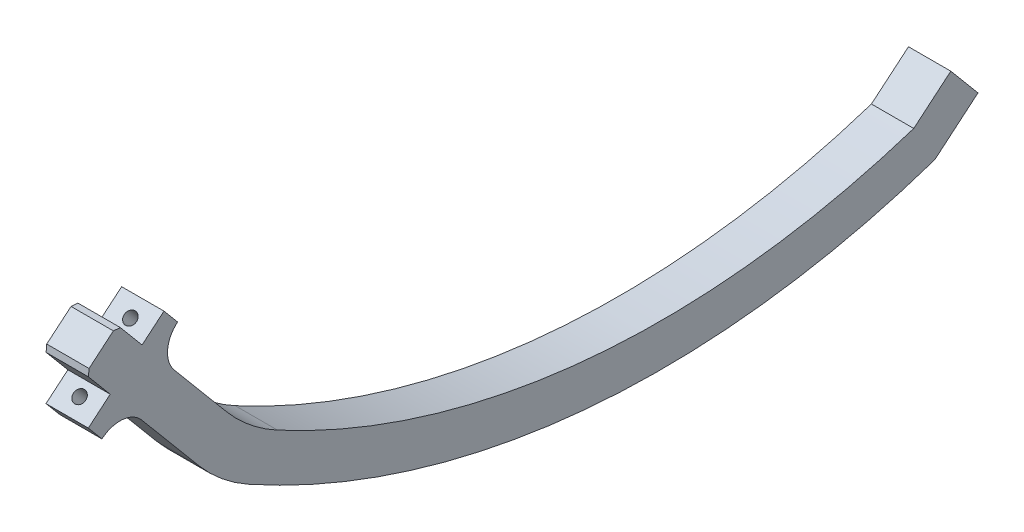
SolidWorks part; units mm, degrees
ref_plane "Ebene vorne" through (0, 0, 0) normal (0, 0, 1) x (1, 0, 0)
ref_plane "Ebene oben" through (0, 0, 0) normal (0, 1, 0) x (1, 0, 0)
ref_plane "Ebene rechts" through (0, 0, 0) normal (1, 0, 0) x (0, 0, -1)
sketch "Skizze1" plane through (0, 0, 0) normal (1, 0, 0) x (0, 0, -1)
  line L0 (0, 12) -> (-233.4212, 12) construction
  line L1 (-240, 65) -> (-230.7357, 72.7737)
  line L2 (0, 12) -> (-3.7358, 23.4037)
  line L3 (0, 12) -> (0, 39.1297) construction
  line L4 (0, 0) -> (-218.6687, 0) construction
  arc A0 (0, 12) -> (-240, 65) centre (-75.176, 241.4765) cw
  arc A1 (-3.7358, 23.4037) -> (-230.7357, 72.7737) centre (-75.176, 241.4765) cw
  dimension "D1" = 53
  dimension "D2" = 240
  dimension "D3" = 40
  dimension "D4" = 12
  dimension "D5" = 12
extrude "Aufsatz-Linear austragen1" add sketch "Skizze1" along normal blind 12
sketch "Skizze4" plane through (0, 0, 0) normal (1, 0, 0) x (0, 0, -1)
  line L0 (-230.7357, 72.7737) -> (-240, 65) construction
  line L2 (-3.7358, 23.4037) -> (6.769, 32.2183)
  line L3 (6.769, 32.2183) -> (14.4825, 23.0258)
  line L4 (14.4825, 23.0258) -> (2.2258, 12.7411)
  line L5 (-3.7358, 23.4037) -> (0, 12)
  arc A0 (0, 12) -> (2.2258, 12.7411) centre (-75.176, 241.4765) ccw
  arc A4 (-240, 65) -> (0, 12) centre (-75.176, 241.4765) ccw construction
  dimension "D1" = 16
  dimension "D2" = 12
extrude "Aufsatz-Linear austragen3" add sketch "Skizze4" along normal blind 12
sketch "Skizze5" plane through (12, 0, 0) normal (1, 0, 0) x (0, 0, -1)
  line L0 (-231.6625, 71.996) -> (-222.47, 79.7094)
  line L1 (-230.7357, 72.7737) -> (-232.109, 74.04) construction
  line L2 (-231.6625, 71.996) -> (-220.0923, 58.2072)
  line L3 (-230.7357, 72.7737) -> (-240, 65) construction
  line L4 (-222.47, 79.7094) -> (-210.8998, 65.9206)
  line L5 (-220.0923, 58.2072) -> (-192.9483, 44.5269)
  line L6 (-220.0923, 58.2072) -> (-211.3409, 65.5505) construction
  line L7 (-210.8998, 65.9206) -> (-192.9483, 44.5269)
  arc A6 (-230.7357, 72.7737) -> (-3.7358, 23.4037) centre (-75.176, 241.4765) ccw construction
  dimension "D1" = 12
  dimension "D2" = 1.2
  dimension "D3" = 18
extrude "Aufsatz-Linear austragen4" add sketch "Skizze5" against normal up to surface (12 mm away) up to face at (0, 27.4794, 77.4862)
sketch "Skizze6" plane through (12, 0, 0) normal (1, 0, 0) x (0, 0, -1)
  line L0 (-231.6625, 71.996) -> (-199.5106, 33.6789)
  line L1 (-199.5106, 33.6789) -> (-204.3677, 29.6033)
  line L2 (-204.3677, 29.6033) -> (-240, 65)
  line L3 (-240, 65) -> (-231.6625, 71.996)
extrude "Schnitt-Linear austragen1" cut sketch "Skizze6" against normal through all
sketch "Skizze7" plane through (12, 0, 0) normal (1, 0, 0) x (0, 0, -1)
  line L0 (-222.47, 79.7094) -> (-229.5406, 88.1359)
  line L1 (-192.9483, 44.5269) -> (-222.47, 79.7094) construction
  line L2 (-229.5406, 88.1359) -> (-238.7332, 80.4225)
  line L3 (-238.7332, 80.4225) -> (-231.6625, 71.996)
  line M4 (-222.47, 79.7094) -> (-231.6625, 71.996)
  dimension "D1" = 11
extrude "Aufsatz-Linear austragen5" [suppressed] add sketch "Skizze7" against normal up to surface (12 mm away) contours L2 L3 L0 M4
fillet "Verrundung1" radius 50 2 edges at (6, 35.2854, 200.8587) (6, 44.5269, 192.9483)
sketch "Skizze8" [suppressed] plane through (0, -76.6111, 91.3015) normal (0, 0.6428, -0.766) x (-1, 0, 0)
  line L0 (-6, 215.0619) -> (-6, 184.7045) construction
  line L1 (0, 215.0619) -> (-12, 215.0619) construction
  circle A0 centre (-6, 210.0619) radius 1.55
  dimension "D2" = 3.1
  dimension "D1" = 5
extrude "Schnitt-Linear austragen2" [suppressed] cut sketch "Skizze8" against normal blind 6
sketch "Skizze9" plane through (0, 156.3205, 131.1685) normal (0, 0.766, 0.6428) x (1, 0, 0)
  line L0 (6, -119.1857) -> (6, -131.1857) construction
  line L1 (0, -119.1857) -> (12, -119.1857) construction
  line L2 (0, -131.1857) -> (12, -131.1857) construction
  line L3 (12, -125.1857) -> (0, -125.1857) construction
  line L4 (12, -119.1857) -> (12, -131.1857) construction
  line L5 (0, -119.1857) -> (0, -131.1857) construction
  line L7 (0, -131.1857) -> (12, -131.1857)
  line L8 (0, -131.1857) -> (0, -119.1857)
  line L9 (0, -119.1857) -> (12, -119.1857)
  line L10 (12, -131.1857) -> (12, -119.1857)
  line L11 (0, -131.1857) -> (12, -119.1857) construction
  line L12 (0, -119.1857) -> (12, -131.1857) construction
  point P12 (6, -125.1857)
  dimension "D1" = 12
extrude "Aufsatz-Linear austragen6" add sketch "Skizze9" along normal blind 11
sketch "Skizze10" plane through (0, 0, 0) normal (-1, 0, 0) x (0, 0, 1)
  line L0 (231.6625, 71.996) -> (237.7909, 66.8537)
  line L1 (229.5406, 88.1359) -> (238.7332, 80.4225) construction
  line L2 (237.7909, 66.8537) -> (233.9341, 62.2574)
  line L3 (238.7332, 80.4225) -> (206.4468, 41.9451) construction
  line L4 (233.9341, 62.2574) -> (227.8058, 67.3997) construction
  line L5 (227.8058, 67.3997) -> (222.6635, 61.2714) construction
  line L6 (222.6635, 61.2714) -> (231.6625, 71.996)
  line L7 (234.1369, 84.2792) -> (238.5201, 89.5029) construction
  line L8 (218.6133, 75.1132) -> (213.471, 68.9848) construction
  line L9 (212.4849, 80.2555) -> (218.6133, 75.1132) construction
  line L10 (213.471, 68.9848) -> (222.47, 79.7094)
  line L11 (216.3416, 84.8517) -> (212.4849, 80.2555)
  line L12 (222.47, 79.7094) -> (216.3416, 84.8517)
  arc A0 (233.9341, 62.2574) -> (222.6635, 61.2714) centre (228.7918, 56.1291) ccw
  arc A1 (212.4849, 80.2555) -> (213.471, 68.9848) centre (207.3426, 74.1271) cw
  dimension "D1" = 6
  dimension "D2" = 8
  dimension "D3" = 11
extrude "Aufsatz-Linear austragen7" add sketch "Skizze10" against normal up to vertex (12 mm away)
sketch "Skizze11" plane through (0, 156.3205, 131.1685) normal (0, 0.766, 0.6428) x (1, 0, 0)
  line L0 (6, -119.1857) -> (6, -108.0662) construction
  line L1 (12, -119.1857) -> (0, -119.1857) construction
  line L2 (12, -125.1857) -> (20.5212, -125.1857) construction
  line L3 (12, -131.1857) -> (12, -119.1857) construction
  circle A0 centre (6, -115.7857) radius 1.75
  circle A1 centre (6, -134.5857) radius 1.75
  dimension "D1" = 3.5
  dimension "D2" = 3.4
extrude "Schnitt-Linear austragen3" cut sketch "Skizze11" against normal blind 10
ref_plane "Ebene1" through (0, 148.6601, 124.7406) normal (0, 0.766, 0.6428) x (1, 0, 0)
sketch "Skizze12" plane through (0, 148.6601, 124.7406) normal (0, 0.766, 0.6428) x (1, 0, 0)
  line L0 (12, -125.1857) -> (17.337, -125.1857) construction
  line L1 (12, -131.1857) -> (12, -119.1857) construction
  circle A0 centre (6, -134.5857) radius 2.75
  circle A1 centre (6, -115.7857) radius 2.75
  dimension "D1" = 5.5
extrude "Schnitt-Linear austragen4" cut sketch "Skizze12" along normal blind 3.6
chamfer "Fase1" distance 1.5 angle 45 2 edges at (6, 88.1359, 229.5406) (6, 80.4225, 238.7332)
sketch "Skizze16" plane through (12, 0, 0) normal (1, 0, 0) x (0, 0, -1)
  line L0 (-222.47, 79.7094) -> (-222.5466, 79.6452)
  line L1 (-222.5466, 79.6452) -> (-228.7173, 86.9992)
  line L2 (-228.5765, 86.9869) -> (-230.6897, 87.1717) construction
  line L3 (-228.7173, 86.9992) -> (-228.6407, 87.0635)
  line L4 (-228.6407, 87.0635) -> (-222.47, 79.7094)
  line L5 (-222.47, 79.7094) -> (-228.5765, 86.9869) construction
  line L6 (-222.47, 79.7094) -> (-216.3416, 84.8517) construction
  line L7 (-234.1369, 84.2792) -> (-224.5632, 72.8697) construction
  line L8 (-237.5841, 81.3866) -> (-230.6897, 87.1717) construction
  line L9 (-237.8333, 79.35) -> (-231.6625, 71.996)
  line L10 (-237.7567, 79.4143) -> (-237.8333, 79.35)
  line L11 (-231.5859, 72.0603) -> (-237.7567, 79.4143)
  line L12 (-231.6625, 71.996) -> (-231.5859, 72.0603)
  dimension "D1" = 0.1
extrude "Schnitt-Linear austragen8" cut sketch "Skizze16" against normal through all
sketch "Skizze17" plane through (12, 0, 0) normal (1, 0, 0) x (0, 0, -1)
  line L0 (-223.0311, 45.9118) -> (-197.0813, 68.6509)
  line L1 (-197.0813, 68.6509) -> (28.1146, 79.9309)
  line L2 (28.1146, 79.9309) -> (56.5334, -12.5859)
  line L3 (56.5334, -12.5859) -> (-151.596, -41.8366)
  line L4 (-151.596, -41.8366) -> (-223.0311, 45.9118)
extrude "Schnitt-Linear austragen9" [suppressed] cut sketch "Skizze17" against normal through all
